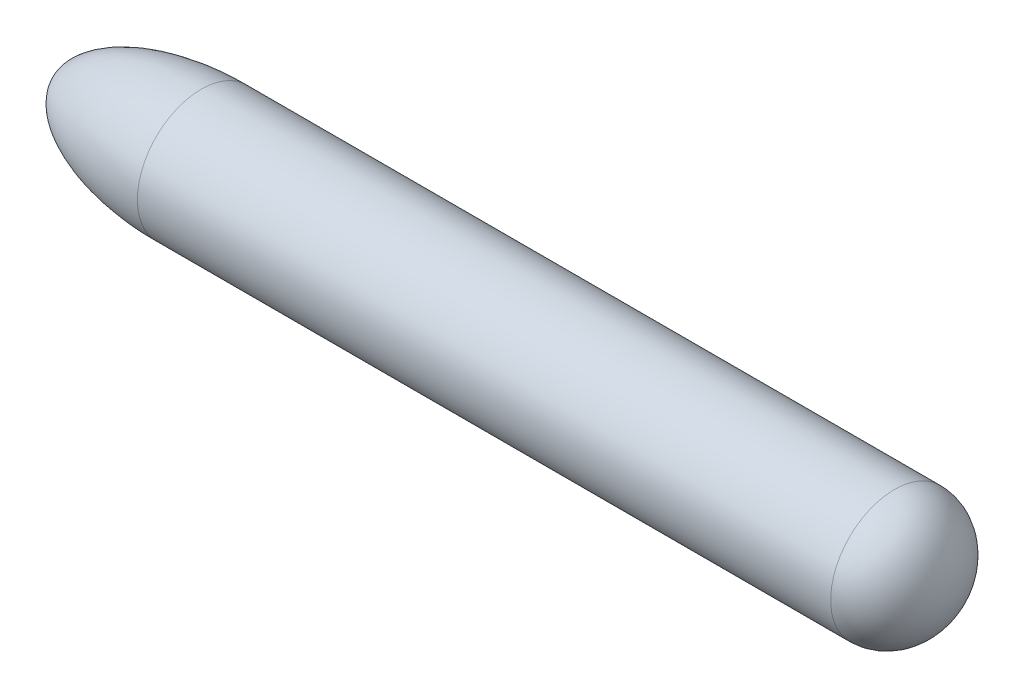
SolidWorks part; units mm, degrees
ref_plane "Front Plane" through (0, 0, 0) normal (0, 0, 1) x (1, 0, 0)
ref_plane "Top Plane" through (0, 0, 0) normal (0, 1, 0) x (1, 0, 0)
ref_plane "Right Plane" through (0, 0, 0) normal (1, 0, 0) x (0, 0, -1)
sketch "Sketch1" plane through (0, 0, 0) normal (1, 0, 0) x (0, 0, -1)
  circle A0 centre (0, 0) radius 115
extrude "Boss-Extrude2" add sketch "Sketch1" along normal blind 761.29
sketch "Sketch2" plane through (0, 0, 0) normal (1, 0, 0) x (0, 0, -1)
  circle A0 centre (0, 0) radius 115
extrude "Boss-Extrude3" add sketch "Sketch2" against normal blind 487.1
sketch "Sketch3" plane through (0, 0, 0) normal (0, 1, 0) x (1, 0, 0)
  line L0 (761.29, 0) -> (761.29, 50000) construction
  line L1 (761.29, -115) -> (761.29, 115) construction
  line L2 (761.29, 0) -> (858.06, 0)
  line L3 (761.29, 0) -> (761.29, 115)
  ellipse E0 centre (761.29, 0) end of major axis (761.29, 115) minor radius 96.77 (761.29, 115) -> (858.06, 0) cw
  point P4 (761.29, 0)
  dimension "D1" = 96.77
revolve "Revolve1" add sketch "Sketch3" angle 360 about L2
sketch "Sketch4" plane through (0, 0, 0) normal (0, 1, 0) x (1, 0, 0)
  line L0 (858.06, 0) -> (-487.1, 0) construction
  line L1 (-487.1, 115) -> (-487.1, -115) construction
  line L2 (-487.1, 0) -> (-741.94, 0)
  line L3 (-487.1, 0) -> (-487.1, -115)
  ellipse E0 centre (-487.1, 0) end of major axis (-741.94, 0) minor radius 115 (-487.1, -115) -> (-741.94, 0) cw
revolve "Revolve2" add sketch "Sketch4" angle 360 about L0
